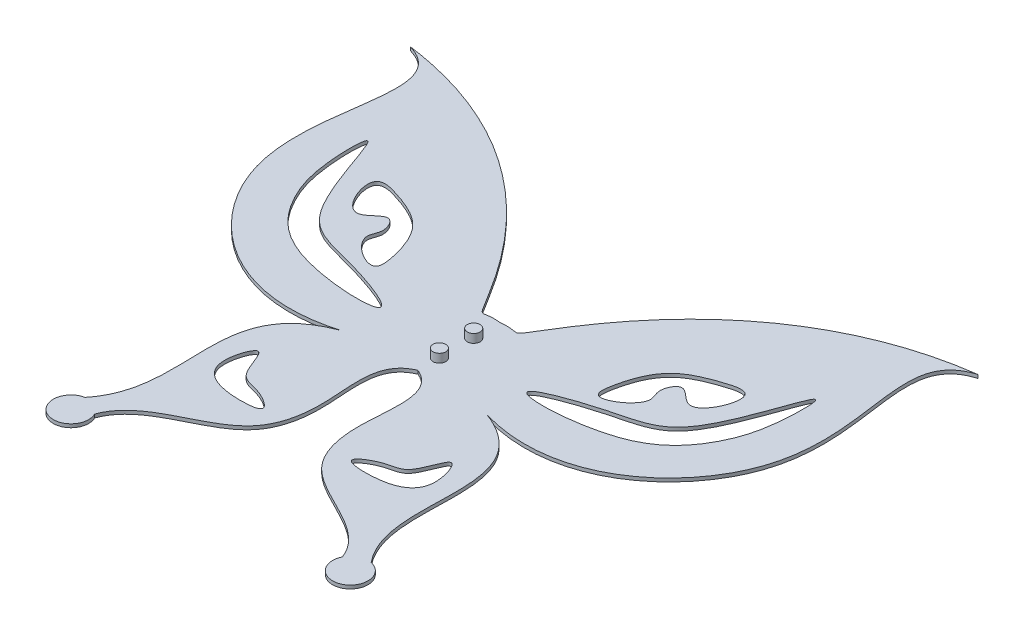
SolidWorks part; units mm, degrees
ref_plane "Top Plane" through (0, 0, 0) normal (0, 0, 1) x (1, 0, 0)
ref_plane "Front Plane" through (0, 0, 0) normal (0, 1, 0) x (1, 0, 0)
ref_plane "Right Plane" through (0, 0, 0) normal (1, 0, 0) x (0, 0, -1)
sketch "Sketch1" plane through (0, 0, 0) normal (0, 1, 0) x (1, 0, 0)
  line L0 (0, 0) -> (0, -19.2191) construction
  arc A0 (28.888, -65.7722) -> (33.3962, -63.5513) centre (32.5907, -67.6022) ccw
  arc A1 (-28.888, -65.7722) -> (-33.3962, -63.5513) centre (-32.5907, -67.6022) cw
  spline S0 degree 3 poles (66.1993, 45.2718) (25.1888, 39.7601) (2.8211, -5.2886) (3.9751, 0.4627) (0, 0) knots 0 0 0 0 0.746463 1 1 1 1
  spline S1 degree 3 poles (66.1993, 45.2718) (51.6167, 40.8827) (68.6229, 18.0833) (51.2206, -15.2951) (34.2777, -25.1159) (17.1688, -20.1995) knots 0 0 0 0 0.577712 0.654586 0.981175 0.981175 0.981175 0.981175
  spline S2 degree 3 poles (17.1688, -20.1995) (25.6019, -23.4169) (31.9303, -36.8217) (26.5797, -55.235) (33.3962, -63.5513) knots 0.041704 0.041704 0.041704 0.041704 0.422179 1 1 1 1
  spline S3 degree 3 poles (0, -19.2191) (6.7629, -22.0653) (2.943, -35.2446) (7.2663, -55.5187) (25.6601, -57.0162) (28.888, -65.7722) knots 0 0 0 0 0.333933 0.545149 1 1 1 1
  spline S4 degree 3 poles (0, -19.2191) (-6.7629, -22.0653) (-2.943, -35.2446) (-7.2663, -55.5187) (-25.6601, -57.0162) (-28.888, -65.7722) knots 0 0 0 0 0.333933 0.545149 1 1 1 1
  spline S5 degree 3 poles (-17.1688, -20.1995) (-25.6019, -23.4169) (-31.9303, -36.8217) (-26.5797, -55.235) (-33.3962, -63.5513) knots 0.041703 0.041703 0.041703 0.041703 0.422179 1 1 1 1
  spline S6 degree 3 poles (-66.1993, 45.2718) (-25.1888, 39.7601) (-2.8211, -5.2886) (-3.9751, 0.4627) (0, 0) knots 0 0 0 0 0.746463 1 1 1 1
  spline S7 degree 3 poles (-66.1993, 45.2718) (-51.6167, 40.8827) (-68.6229, 18.0833) (-51.2206, -15.2951) (-34.2777, -25.1159) (-17.1688, -20.1995) knots 0 0 0 0 0.577712 0.654586 0.981175 0.981175 0.981175 0.981175
  spline S8 degree 3 poles (7.4688, -12.9176) (31.7676, -4.3007) (45.9005, -2.6179) (53.2309, 31.3533) (52.8097, 9.4792) (48.8466, -0.8286) (39.5649, -11.83) (7.4688, -12.9176) (31.7676, -4.3007) (45.9005, -2.6179) knots -0.467414 -0.32234 -0.129732 0 0.135006 0.342905 0.450287 0.532586 0.67766 0.870268 1 1.135006 1.342905 1.450287 only from (30.0107, -5.3715) to (30.0107, -5.3715)
  spline S9 degree 3 poles (-7.4688, -12.9176) (-31.7676, -4.3007) (-45.9005, -2.6179) (-53.2309, 31.3533) (-52.8097, 9.4792) (-48.8466, -0.8286) (-39.5649, -11.83) (-7.4688, -12.9176) (-31.7676, -4.3007) (-45.9005, -2.6179) knots -0.467414 -0.32234 -0.129732 0 0.135006 0.342905 0.450287 0.532586 0.67766 0.870268 1 1.135006 1.342905 1.450287 only from (-30.0107, -5.3715) to (-30.0107, -5.3715)
  spline S10 degree 3 poles (24.6832, -6.225) (26.2539, 3.5333) (29.132, 10.141) (35.871, 13.336) (46.3501, 16.3519) (39.9756, 0.9673) (34.2985, 10.1927) (31.6305, 4.7927) (34.898, 0.3974) (24.6832, -6.225) (26.2539, 3.5333) (29.132, 10.141) knots -0.270015 -0.220208 -0.069517 0 0.165089 0.316757 0.408386 0.575943 0.666416 0.729985 0.779792 0.930483 1 1.165089 1.316757 1.408386 only from (25.9338, 0.9434) to (25.9338, 0.9434)
  spline S11 degree 3 poles (-24.6832, -6.225) (-26.2539, 3.5333) (-29.132, 10.141) (-35.871, 13.336) (-46.3501, 16.3519) (-39.9756, 0.9673) (-34.2985, 10.1927) (-31.6305, 4.7927) (-34.898, 0.3974) (-24.6832, -6.225) (-26.2539, 3.5333) (-29.132, 10.141) knots -0.270015 -0.220208 -0.069517 0 0.165089 0.316757 0.408386 0.575943 0.666416 0.729985 0.779792 0.930483 1 1.165089 1.316757 1.408386 only from (-25.9338, 0.9434) to (-25.9338, 0.9434)
  spline S12 degree 3 poles (14.7439, -41.4481) (7.9161, -45.7302) (18.7592, -46.5457) (26.6582, -43.3249) (22.1306, -30.0302) (20.138, -41.5888) (14.7439, -41.4481) (7.9161, -45.7302) (18.7592, -46.5457) knots -0.43195 -0.248359 -0.125681 0 0.139258 0.407259 0.56805 0.751641 0.874319 1 1.139258 1.407259 1.56805 only from (10.4185, -45.0128) to (10.4185, -45.0128)
  spline S13 degree 3 poles (-14.7439, -41.4481) (-7.9161, -45.7302) (-18.7592, -46.5457) (-26.6582, -43.3249) (-22.1306, -30.0302) (-20.138, -41.5888) (-14.7439, -41.4481) (-7.9161, -45.7302) (-18.7592, -46.5457) knots -0.43195 -0.248359 -0.125681 0 0.139258 0.407259 0.56805 0.751641 0.874319 1 1.139258 1.407259 1.56805 only from (-10.4185, -45.0128) to (-10.4185, -45.0128)
  dimension "D1" = 150
extrude "Boss-Extrude3" add sketch "Sketch1" along normal blind 0.8
sketch "Harness" plane through (0, 0.8, 0) normal (0, 1, 0) x (1, 0, 0)
  line L0 (0, 3.2593) -> (0, -19.2191) construction
  circle A0 centre (0, -6.2191) radius 1.5
  circle A1 centre (0, -14.2191) radius 1.5
  dimension "D3" = 3
  dimension "D1" = 8
  dimension "D2" = 5
extrude "Boss-Extrude4" add sketch "Harness" along normal blind 2
